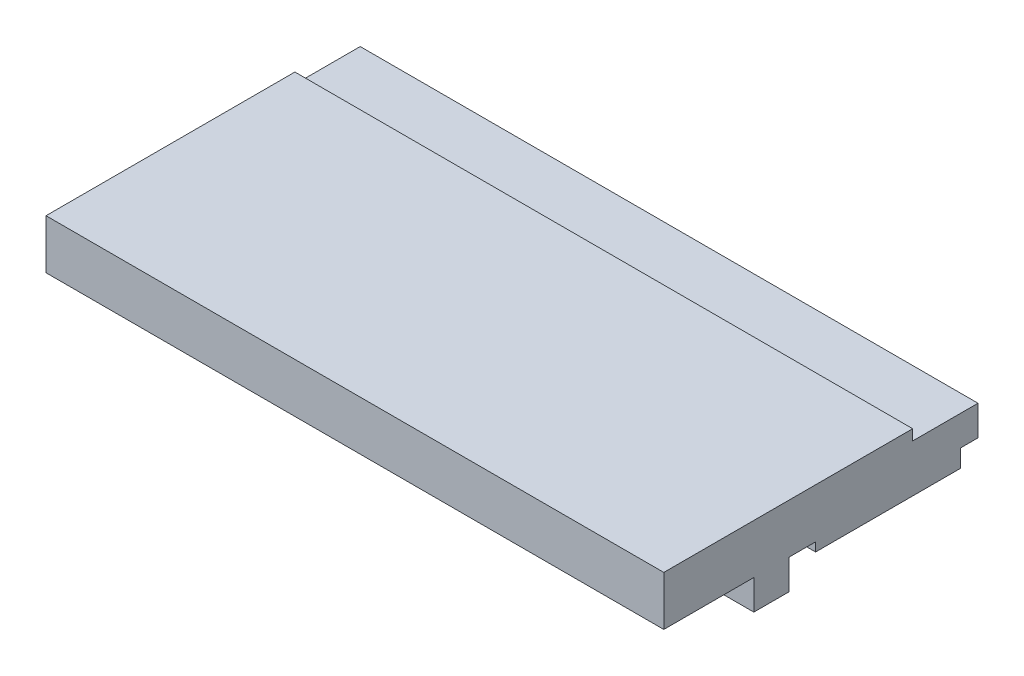
SolidWorks part; units mm, degrees
ref_plane "Front Plane" through (0, 0, 0) normal (0, 0, 1) x (1, 0, 0)
ref_plane "Top Plane" through (0, 0, 0) normal (0, 1, 0) x (1, 0, 0)
ref_plane "Right Plane" through (0, 0, 0) normal (1, 0, 0) x (0, 0, -1)
sketch "Sketch2" plane through (0, 0, 0) normal (1, 0, 0) x (0, 0, -1)
  line L0 (0, 0) -> (0, -17)
  line L1 (0, -17) -> (-10, -17)
  line L2 (-10, -17) -> (-10, -27)
  line L3 (0, 0) -> (-37, 0)
  line L4 (-37, 0) -> (-37, 6)
  line L5 (-37, 6) -> (-178, 6)
  line L6 (-10, -27) -> (-92, -27)
  line L7 (-92, -27) -> (-92, -22)
  line L8 (-92, -22) -> (-107, -22)
  line L9 (-107, -22) -> (-107, -39)
  line L12 (-107, -39) -> (-127, -39)
  line L13 (-127, -39) -> (-127, -22)
  line L14 (-127, -22) -> (-178, -22)
  line L15 (-178, -22) -> (-178, 6)
  dimension "D1" = 17
  dimension "D2" = 10
  dimension "D3" = 10
  dimension "D4" = 37
  dimension "D5" = 6
  dimension "D6" = 141
  dimension "D7" = 82
  dimension "D8" = 5
  dimension "D9" = 15
  dimension "D10" = 17
  dimension "D11" = 20
  dimension "D12" = 17
extrude "Boss-Extrude1" add sketch "Sketch2" along normal blind 350
